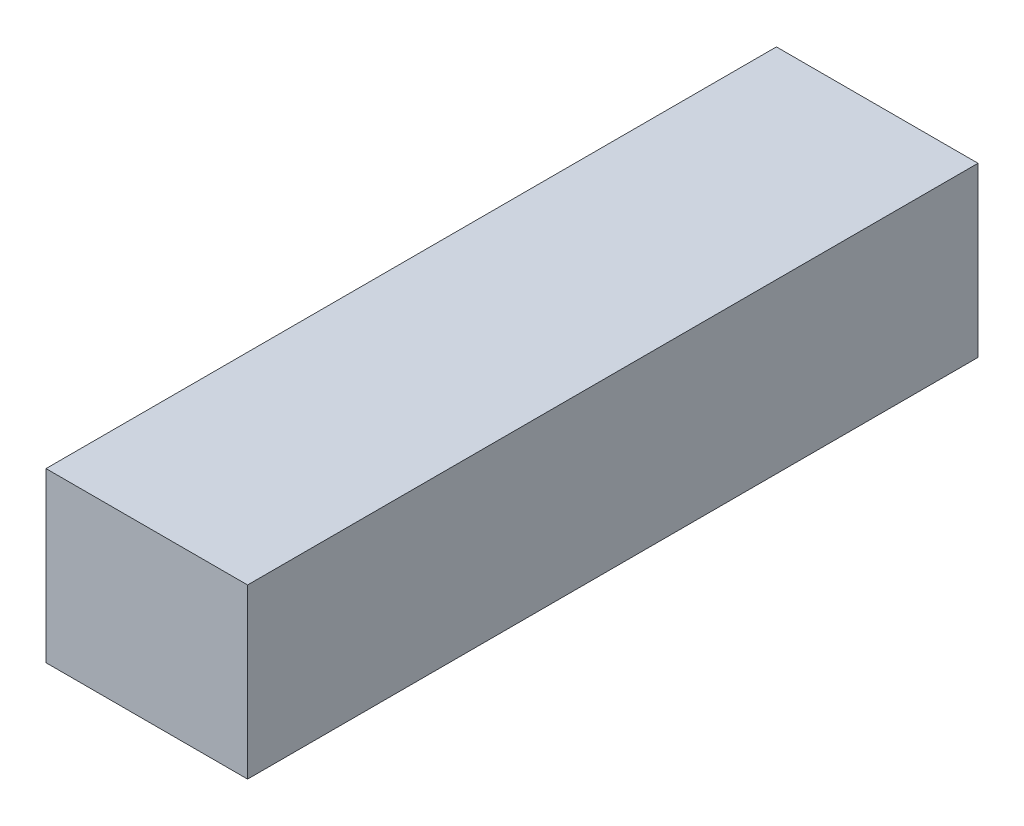
SolidWorks part; units mm, degrees
ref_plane "Plan de face" through (0, 0, 0) normal (0, 0, 1) x (1, 0, 0)
ref_plane "Plan de dessus" through (0, 0, 0) normal (0, 1, 0) x (1, 0, 0)
ref_plane "Plan de droite" through (0, 0, 0) normal (1, 0, 0) x (0, 0, -1)
sketch "Sketch1" plane through (0, 0, 0) normal (0, 1, 0) x (1, 0, 0)
  line L1 (-15.225, -55.165) -> (15.225, -55.165)
  line L2 (-15.225, -55.165) -> (-15.225, 55.165)
  line L3 (-15.225, 55.165) -> (15.225, 55.165)
  line L4 (15.225, -55.165) -> (15.225, 55.165)
  line L5 (-15.225, -55.165) -> (15.225, 55.165) construction
  line L6 (-15.225, 55.165) -> (15.225, -55.165) construction
  point P0 (0, 0)
  dimension "D1" = 30.45
  dimension "D2" = 110.33
extrude "Boss-Extrude1" add sketch "Sketch1" along normal blind 25.4
